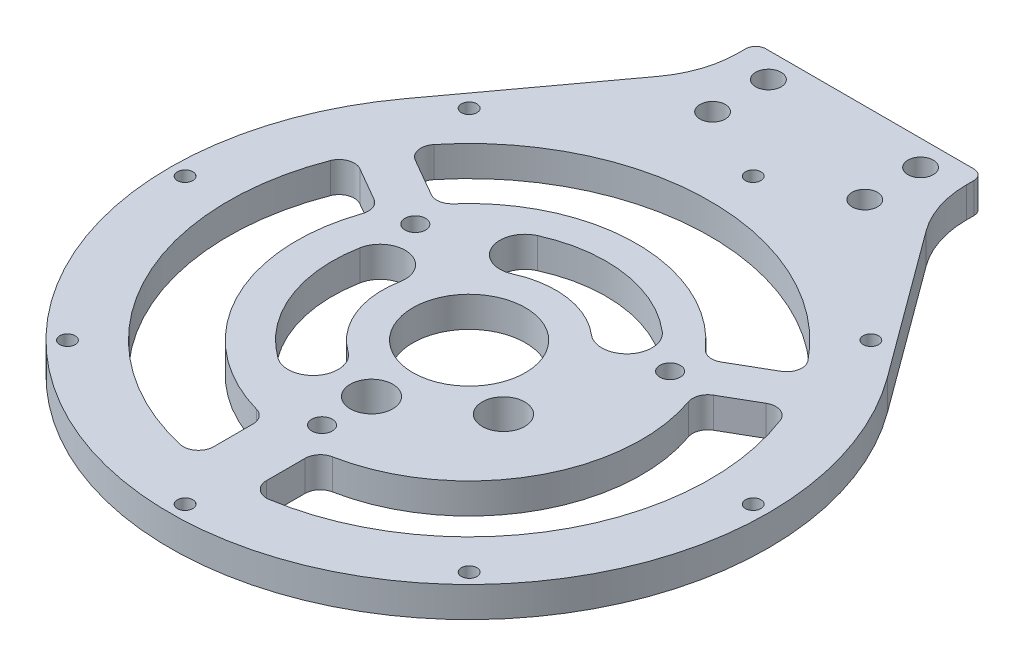
SolidWorks part; units mm, degrees
material "Thornel Mat VMA"
ref_plane "前视基准面" through (0, 0, 0) normal (0, 0, 1) x (1, 0, 0)
ref_plane "上视基准面" through (0, 0, 0) normal (0, 1, 0) x (1, 0, 0)
ref_plane "右视基准面" through (0, 0, 0) normal (1, 0, 0) x (0, 0, -1)
other "Configuration Table"
sketch "草图1" plane through (0, 0, 0) normal (0, 1, 0) x (1, 0, 0)
  circle A0 centre (0, 0) radius 53 construction
  circle A1 centre (0, 0) radius 59
  circle A2 centre (0, 0) radius 11.1
  dimension "D1" = 106
  dimension "D3" = 22.2
  dimension "D2" = 6
extrude "凸台-拉伸1" add sketch "草图1" along normal blind 6
sketch "草图2" plane through (0, 6, 0) normal (0, 1, 0) x (1, 0, 0)
  circle A0 centre (0, 0) radius 56 construction
  circle A1 centre (0, 0) radius 59 construction
  circle A2 centre (0, 56) radius 1.525
  circle A3 centre (39.598, 39.598) radius 1.525
  circle A4 centre (56, 0) radius 1.525
  circle A5 centre (39.598, -39.598) radius 1.525
  circle A6 centre (0, -56) radius 1.525
  circle A7 centre (-39.598, -39.598) radius 1.525
  circle A8 centre (-56, 0) radius 1.525
  circle A9 centre (-39.598, 39.598) radius 1.525
  point P23 (0, 0)
  dimension "D1" = 3
  dimension "D2" = 3.05
  dimension "D3" = 8
extrude "切除-拉伸1" cut sketch "草图2" against normal blind 6
sketch "草图3" plane through (0, 6, 0) normal (0, 1, 0) x (1, 0, 0)
  line L0 (-51.0881, 29.5129) -> (-22.5, 79)
  line L1 (-22.5, 79) -> (22.5, 79)
  line L2 (22.5, 79) -> (51.0881, 29.5129)
  line L3 (0, 79) -> (0, 0) construction
  circle A0 centre (0, 0) radius 59 construction
  arc A1 (51.0881, 29.5129) -> (-51.0881, 29.5129) centre (0, 0) ccw
  dimension "D1" = 20
  dimension "D2" = 45
extrude "凸台-拉伸2" add sketch "草图3" against normal blind 6
sketch "草图4" plane through (0, 0, 0) normal (0, -1, 0) x (1, 0, 0)
  circle A0 centre (25.1147, -14.5) radius 2.1 construction
  circle A1 centre (-25.1147, -14.5) radius 2.1 construction
  circle A2 centre (0, 29) radius 2.1 construction
  circle A3 centre (0, 19.25) radius 4 construction
  circle A4 centre (25.1147, -14.5) radius 2.1 construction
  circle A5 centre (-25.1147, -14.5) radius 2.1 construction
  circle A6 centre (0, 29) radius 2.1 construction
  circle A7 centre (0, 19.25) radius 4 construction
  circle A8 centre (0, 19.25) radius 4.2
  circle A9 centre (0, 29) radius 2.025
  circle A10 centre (25.1147, -14.5) radius 2.025
  circle A11 centre (-25.1147, -14.5) radius 2.025
  dimension "D1" = 4.05
  dimension "D2" = 0.2
extrude "切除-拉伸2" cut sketch "草图4" against normal blind 6
sketch "草图5" plane through (0, 0, 0) normal (0, -1, 0) x (1, 0, 0)
  line L0 (16.2803, 12.4017) -> (15.7626, 6.0983) construction
  line L4 (16.0126, 5.6653) -> (19.1303, 7.4653)
  line L5 (19.3133, 8.1483) -> (16.7133, 12.6517)
  line L6 (16.0303, 12.8347) -> (12.9126, 11.0347)
  line L7 (12.7296, 10.3517) -> (15.3296, 5.8483)
  line L8 (16.0126, 5.6653) -> (19.1303, 7.4653) construction
  line L9 (19.3133, 8.1483) -> (16.7133, 12.6517) construction
  line L10 (16.0303, 12.8347) -> (12.9126, 11.0347) construction
  line L11 (12.7296, 10.3517) -> (15.3296, 5.8483) construction
  circle A0 centre (16.0215, 9.25) radius 4.2
  circle A1 centre (0, 19.25) radius 4.2 construction
  arc A5 (19.1303, 7.4653) -> (19.3133, 8.1483) centre (18.8803, 7.8983) ccw
  arc A6 (16.7133, 12.6517) -> (16.0303, 12.8347) centre (16.2803, 12.4017) ccw
  arc A7 (12.9126, 11.0347) -> (12.7296, 10.3517) centre (13.1626, 10.6017) ccw
  arc A8 (15.3296, 5.8483) -> (15.5126, 5.6653) centre (15.7626, 6.0983) ccw
  arc A9 (15.5126, 5.6653) -> (16.0126, 5.6653) centre (15.7626, 6.0983) ccw
  arc A10 (19.1303, 7.4653) -> (19.3133, 8.1483) centre (18.8803, 7.8983) ccw construction
  arc A11 (16.7133, 12.6517) -> (16.0303, 12.8347) centre (16.2803, 12.4017) ccw construction
  arc A12 (12.9126, 11.0347) -> (12.7296, 10.3517) centre (13.1626, 10.6017) ccw construction
  arc A13 (15.3296, 5.8483) -> (15.5126, 5.6653) centre (15.7626, 6.0983) ccw construction
  arc A14 (15.5126, 5.6653) -> (16.0126, 5.6653) centre (15.7626, 6.0983) ccw construction
  dimension "D1" = 0
extrude "切除-拉伸3" cut sketch "草图5" against normal blind 6
sketch "草图8" plane through (0, 0, 0) normal (0, -1, 0) x (1, 0, 0)
  line L0 (0, 0) -> (25.1147, -14.5) construction
  line L1 (0, 0) -> (41.1362, -23.75)
  line L2 (0, 0) -> (-25.1147, -14.5) construction
  line L3 (0, 0) -> (-41.1362, -23.75)
  line L4 (0, -4.6188) -> (-39.1362, -27.2141)
  line L5 (0, -4.6188) -> (39.1362, -27.2141)
  line L6 (0, 4.6188) -> (-43.1362, -20.2859)
  line L7 (0, 4.6188) -> (43.1362, -20.2859)
  line L8 (0, 0) -> (0, 47.5) construction
  circle A0 centre (0, 0) radius 47.5
  circle A1 centre (0, 0) radius 33
  circle A3 centre (0, 0) radius 29 construction
  dimension "D1" = 95
  dimension "D4" = 4
  dimension "D2" = 4
  dimension "D3" = 4
extrude "切除-拉伸4" cut sketch "草图8" against normal blind 10 contours A1 L4 A0 L5
sketch "草图9" plane through (0, 0, 0) normal (0, -1, 0) x (1, 0, 0)
  line L0 (0, 0) -> (0, 56) construction
  line L1 (0, 0) -> (25.1147, -14.5) construction
  line L2 (0, 0) -> (41.1362, -23.75) construction
  line L3 (-2, -3.4641) -> (39.1362, -27.2141)
  line L4 (2, 3.4641) -> (43.1362, -20.2859)
  line L5 (4, 0) -> (4, 56)
  line L6 (-4, 0) -> (-4, 56)
  circle A0 centre (0, 0) radius 34
  circle A1 centre (0, 0) radius 29 construction
  circle A2 centre (0, 0) radius 47.5
  dimension "D1" = 5
  dimension "D2" = 95
  dimension "D3" = 4
  dimension "D4" = 4
  dimension "D5" = 4
  dimension "D6" = 4
extrude "切除-拉伸5" cut sketch "草图9" against normal blind 10 contours L4 A2 L5 A0
sketch "草图10" plane through (0, 0, 0) normal (0, -1, 0) x (1, 0, 0)
  line L0 (0, 0) -> (0, 56) construction
  line L1 (0, 0) -> (-25.1147, -14.5) construction
  line L2 (0, 0) -> (-41.1362, -23.75) construction
  line L3 (-2, 3.4641) -> (-43.1362, -20.2859)
  line L4 (2, -3.4641) -> (-39.1362, -27.2141)
  line L5 (4, 0) -> (4, 56)
  line L6 (-7, 0) -> (-7, 56)
  circle A0 centre (0, 0) radius 34
  circle A1 centre (0, 0) radius 47.5
  arc A2 (31.2404, -13.4178) -> (4, 33.7639) centre (0, 0) ccw construction
  dimension "D2" = 95
  dimension "D3" = 4
  dimension "D4" = 4
  dimension "D5" = 4
  dimension "D6" = 7
extrude "切除-拉伸7" cut sketch "草图10" against normal blind 10 contours L6 A1 L3 A0
fillet "圆角1" radius 3 12 edges at (38.9901, 3, -27.1297) (-38.9901, 3, -27.1297) (31.2404, 3, -13.4178) (4, 3, 33.7639) (4, 3, 47.3313) (42.9901, 3, -20.2015) (-7, 3, 33.2716) (-31.2404, 3, -13.4178) (-42.9901, 3, -20.2015) (-7, 3, 46.9814) (26.3681, 3, -19.8424) (-26.3681, 3, -19.8424)
fillet "圆角2" [suppressed] radius 2
sketch "草图11" plane through (0, 6, 0) normal (0, 1, 0) x (1, 0, 0)
  circle A0 centre (15, 63) radius 2.5 construction
  circle A1 centre (15, 74) radius 2.5 construction
  circle A2 centre (-15, 63) radius 2.5 construction
  circle A3 centre (-15, 74) radius 2.5 construction
  circle A4 centre (15, 63) radius 2.5
  circle A5 centre (15, 74) radius 2.5
  circle A6 centre (-15, 63) radius 2.5
  circle A7 centre (-15, 74) radius 2.5
extrude "切除-拉伸8" cut sketch "草图11" against normal blind 10
sketch "草图12" plane through (0, 0, 0) normal (0, -1, 0) x (1, 0, 0)
  arc A0 (-9.0868, -20.0906) -> (14.3896, -16.7076) centre (0, 0) ccw construction
  arc A1 (-11.1267, -24.6008) -> (17.6199, -20.4582) centre (0, 0) ccw
  arc A2 (-7.0469, -15.5805) -> (11.1593, -12.9569) centre (0, 0) ccw
  arc A3 (-7.0469, -15.5805) -> (-11.1267, -24.6008) centre (-9.0868, -20.0906) ccw
  arc A4 (17.6199, -20.4582) -> (11.1593, -12.9569) centre (14.3896, -16.7076) ccw
  arc A5 (-24.825, -21.7421) -> (24.825, -21.7421) centre (0, 0) ccw construction
  circle A6 centre (0, 0) radius 11.1 construction
  circle A9 centre (25.1147, -14.5) radius 2.025 construction
  circle A11 centre (-25.1147, -14.5) radius 2.025 construction
  point P4 (3.145, -21.8246)
  dimension "D1" = 6
  dimension "D2" = 6
  dimension "D3" = 6
  dimension "D4" = 10
extrude "切除-拉伸9" cut sketch "草图12" against normal blind 10
pattern_circular "阵列(圆周)1" count 3 over 360 about axis through (0, 0, 0) along (0, 1, 0) skipping 2 of "切除-拉伸9"
sketch "草图15" plane through (0, 0, 0) normal (0, -1, 0) x (1, 0, 0)
  line L0 (22.5, -79) -> (22.5, -69)
  line L1 (22.5, -69) -> (47.5351, -34.9487)
  line L2 (22.5, -79) -> (51.0881, -29.5129)
  line L3 (0, 0) -> (0, -79) construction
  line L4 (22.5, -79) -> (-22.5, -79) construction
  line L5 (-22.5, -79) -> (-51.0881, -29.5129)
  line L6 (-22.5, -69) -> (-47.5351, -34.9487)
  line L7 (-22.5, -79) -> (-22.5, -69)
  arc A0 (47.5351, -34.9487) -> (51.0881, -29.5129) centre (0, 0) ccw
  arc A1 (-47.5351, -34.9487) -> (-51.0881, -29.5129) centre (0, 0) cw
  dimension "D2" = 10
extrude "切除-拉伸10" cut sketch "草图15" against normal mid plane 40
fillet "圆角3" radius 20 2 edges at (-22.5, 3, -69) (22.5, 3, -69)
fillet "圆角4" radius 2 2 edges at (22.5, 3, -79) (-22.5, 3, -79)
